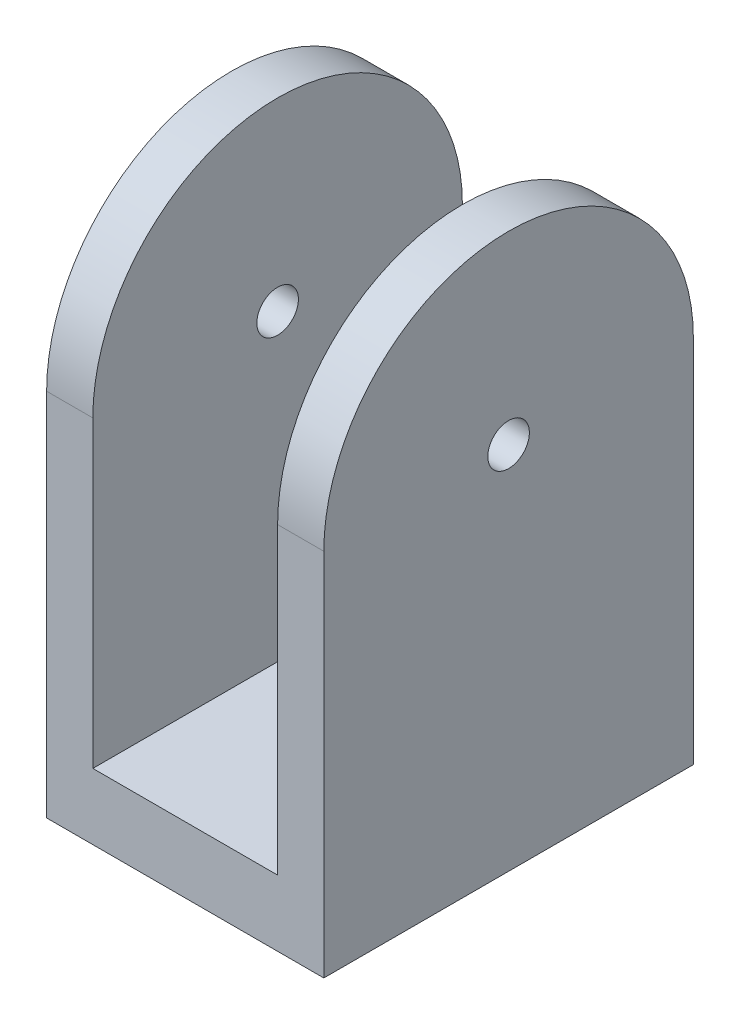
SolidWorks part; units mm, degrees
ref_plane "Front Plane" through (0, 0, 0) normal (0, 0, 1) x (1, 0, 0)
ref_plane "Top Plane" through (0, 0, 0) normal (0, 1, 0) x (1, 0, 0)
ref_plane "Right Plane" through (0, 0, 0) normal (1, 0, 0) x (0, 0, -1)
sketch "Sketch1" plane through (0, 0, 0) normal (1, 0, 0) x (0, 0, -1)
  line L0 (20, 0) -> (-20, 0)
  line L1 (-20, 0) -> (-20, 40)
  line L2 (0, 0) -> (0, 181.7736) construction
  line L3 (20, 0) -> (20, 40)
  arc A3 (-20, 40) -> (20, 40) centre (0, 40) cw
extrude "Boss-Extrude1" add sketch "Sketch1" along normal blind 30
ref_plane "Plane1" through (0, 267.1448, 0) normal (0, 1, 0) x (1, 0, 0)
sketch "Sketch2" plane through (0, 267.1448, 0) normal (0, 1, 0) x (1, 0, 0)
  line L0 (0, 0) -> (30, 0) construction
  line L1 (30, 0) -> (0, 0) construction
  line L2 (15, 20) -> (15, -20) construction
  line L3 (30, 20) -> (0, 20) construction
  line L4 (30, -20) -> (0, -20) construction
  line L5 (0, 20) -> (0, -20) construction
  line L6 (25, -100) -> (5, -100)
  line L7 (25, -100) -> (25, 100)
  line L8 (25, 100) -> (5, 100)
  line L9 (5, -100) -> (5, 100)
  line L10 (25, -100) -> (5, 100) construction
  line L11 (25, 100) -> (5, -100) construction
  line L12 (30, -20) -> (30, 20) construction
  point P11 (15, 0)
  dimension "D1" = 5
  dimension "D2" = 5
extrude "Cut-Extrude1" cut sketch "Sketch2" against normal blind 260
sketch "Sketch3" plane through (0, 0, 0) normal (0, -1, 0) x (1, 0, 0)
  line L0 (0, 0) -> (30, 0) construction
  line L1 (30, 20) -> (30, -20) construction
  circle A0 centre (15, 0) radius 2.25
extrude "Cut-Extrude2" cut sketch "Sketch3" against normal through all
sketch "Sketch5" plane through (30, 0, 0) normal (1, 0, 0) x (0, 0, -1)
  circle A0 centre (0, 40) radius 2.25
extrude "Cut-Extrude3" cut sketch "Sketch5" against normal through all
